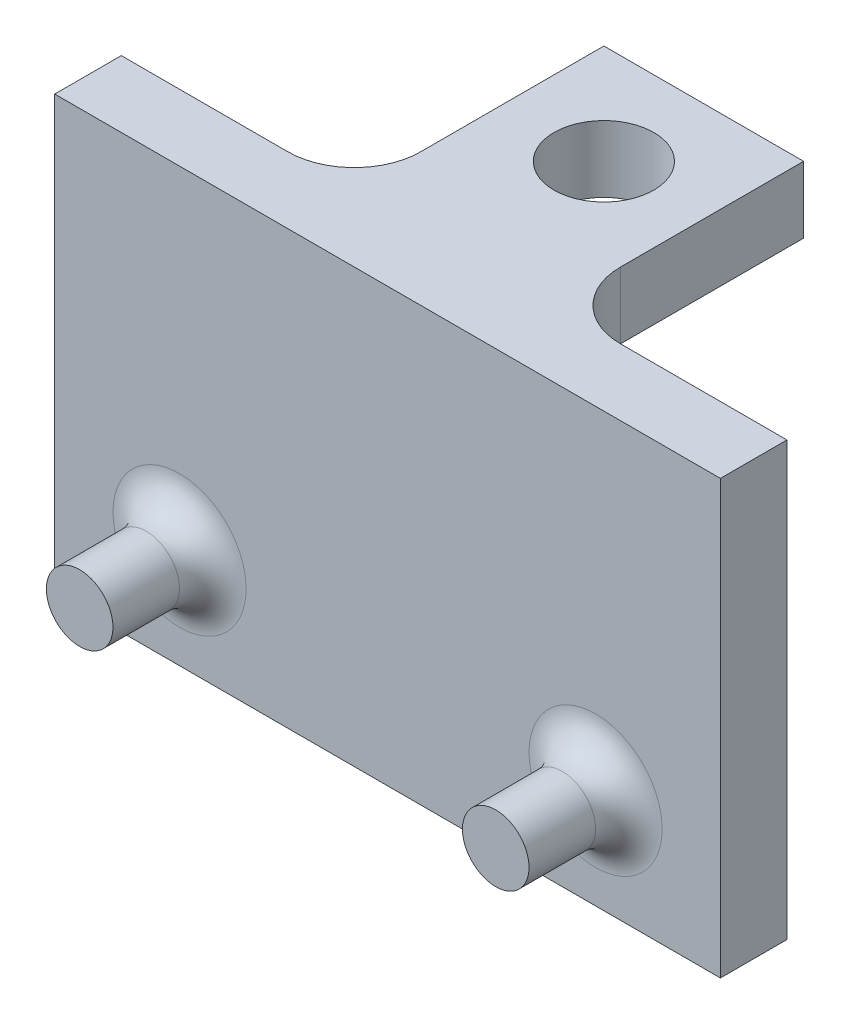
SolidWorks part; units mm, degrees
ref_plane "Plan de face" through (0, 0, 0) normal (0, 0, 1) x (1, 0, 0)
ref_plane "Plan de dessus" through (0, 0, 0) normal (0, 1, 0) x (1, 0, 0)
ref_plane "Plan de droite" through (0, 0, 0) normal (1, 0, 0) x (0, 0, -1)
sketch "Esquisse1" plane through (0, 0, 0) normal (0, 0, 1) x (1, 0, 0)
  line L1 (0, 0) -> (20, 0)
  line L2 (0, 0) -> (0, 11)
  line L3 (0, 11) -> (20, 11)
  line L4 (20, 0) -> (20, 11)
  dimension "D1" = 11
  dimension "D2" = 20
extrude "Boss.-Extru.1" add sketch "Esquisse1" along normal blind 2
sketch "Esquisse2" plane through (0, 0, 2) normal (0, 0, 1) x (1, 0, 0)
  line L0 (0, 0) -> (20, 0) construction
  line L1 (20, 0) -> (20, 11) construction
  line L2 (0, 11) -> (0, 0) construction
  circle A0 centre (16.25, 3) radius 1
  circle A1 centre (3.75, 3) radius 1
  point P8 (0, 0)
  point P9 (0, 0)
  point P10 (0, 0)
  dimension "D1" = 2
  dimension "D2" = 2
  dimension "D3" = 3
  dimension "D4" = 3.75
  dimension "D5" = 12.5
  dimension "D6" = 3.75
  dimension "D7" = 3
extrude "Boss.-Extru.2" add sketch "Esquisse2" along normal blind 3
fillet "Congé1" radius 1 2 edges at (2.75, 3, 2) (15.25, 3, 2)
sketch "Esquisse3" plane through (0, 11, 0) normal (0, 1, 0) x (1, 0, 0)
  line L10 (0, 0) -> (0, -2)
  line L11 (0, -2) -> (20, -2)
  line L12 (20, -2) -> (20, 0)
  line L13 (20, 0) -> (13, 0)
  line L14 (20, 0) -> (0, 0) construction
  line L15 (13, 0) -> (13, 7.5)
  line L16 (13, 7.5) -> (7, 7.5)
  line L17 (7, 7.5) -> (7, 0)
  line L18 (7, 0) -> (0, 0)
  circle A0 centre (10, 4.5) radius 1.5
  dimension "D6" = 3
  dimension "D1" = 6
  dimension "D2" = 7.5
  dimension "D3" = 7
  dimension "D4" = 3
  dimension "D5" = 3
extrude "Boss.-Extru.3" add sketch "Esquisse3" along normal blind 2
fillet "Congé2" radius 2 2 edges at (7, 12, 0) (13, 12, 0)
